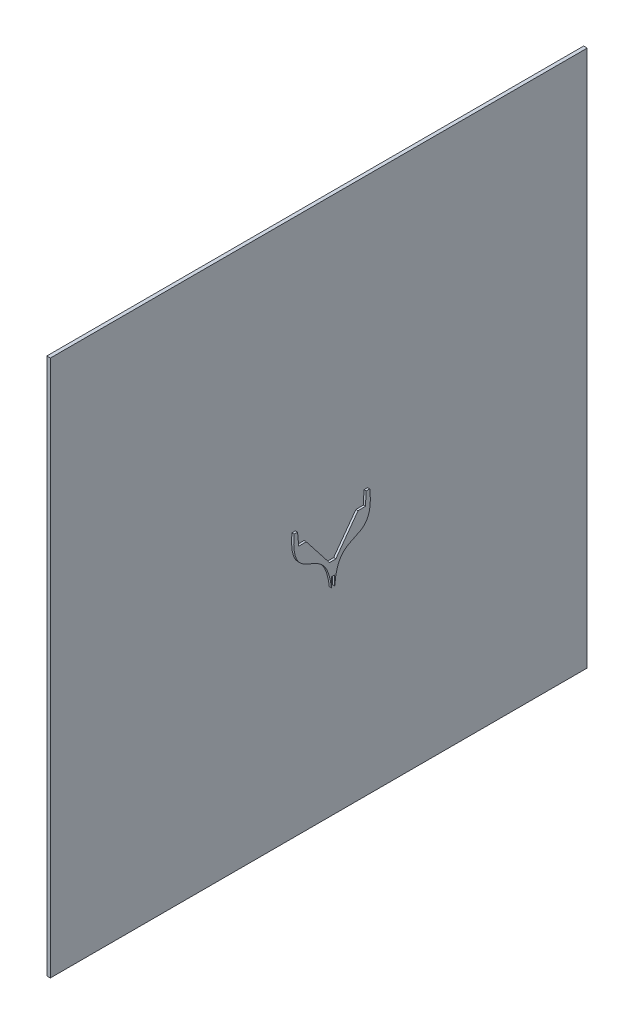
SolidWorks part; units mm, degrees
ref_plane "Plan de face" through (0, 0, 0) normal (0, 0, 1) x (1, 0, 0)
ref_plane "Plan de dessus" through (0, 0, 0) normal (0, 1, 0) x (1, 0, 0)
ref_plane "Plan de droite" through (0, 0, 0) normal (1, 0, 0) x (0, 0, -1)
sketch "Esquisse1" plane through (0, 0, 0) normal (0, 0, 1) x (1, 0, 0)
  point P0 (-20, 0)
  dimension "D1" = 20
sketch3d "Esquisse3D1"
  line L1 (-20, 1121.2893, 777.275) -> (-20, 1121.2893, -722.725)
  line L2 (-20, 1121.2893, 777.275) -> (-20, -378.7107, 777.275)
  line L3 (-20, -378.7107, 777.275) -> (-20, -378.7107, -722.725)
  line L4 (-20, 1121.2893, -722.725) -> (-20, -378.7107, -722.725)
  dimension "D1" = 1500
  dimension "D2" = 1500
extrude "Boss.-Extru.2" add sketch "Esquisse3D1" along direction (1, 0, 0) on the side of the normal blind 10 contours L2 L1 L4 L3
sketch "Esquisse4" plane through (-10, 0, 0) normal (1, 0, 0) x (0, 0, -1)
  line L0 (0, 0) -> (-7.701, 425.1082) construction
  line L1 (169.3944, 339.9131) -> (-188.5193, 333.4294) construction
  line L2 (-187.2006, 249.23) -> (169.0622, 255.6839) construction
  line L3 (-144.268, 175.2448) -> (126.4811, 180.1495) construction
sketch "Esquisse5" plane through (0, 0, 0) normal (1, 0, 0) x (0, 0, -1)
  line L0 (-7.701, 425.1082) -> (0, 0) construction
  line L2 (0, 0) -> (13.2414, 145.149) construction
  line L3 (13.2414, 145.149) -> (-56.4453, 383.7717) construction
  line L4 (-56.4453, 383.7717) -> (120.2156, 187.3517) construction
  line L5 (120.2156, 187.3517) -> (99.0942, 374.657) construction
  line L6 (-8.1043, 252.4744) -> (-1.0453, 252.6023)
  line L8 (99.0942, 374.657) -> (89.0942, 374.4759)
  line L9 (89.0942, 374.4759) -> (87.1184, 338.4227)
  line L10 (169.3944, 339.9131) -> (-188.5193, 333.4294) construction
  line L11 (87.1184, 338.4227) -> (66.3274, 338.046)
  line L12 (66.3274, 338.046) -> (4.2416, 252.6981)
  line L13 (-187.2006, 249.23) -> (169.0622, 255.6839) construction
  line L14 (4.2416, 252.6981) -> (-1.0453, 252.6023)
  line L16 (-144.268, 175.2448) -> (126.4811, 180.1495) construction
  line L18 (0, 0) -> (-18.4898, 144.5742) construction
  line L19 (-18.4898, 144.5742) -> (42.5085, 385.5643) construction
  line L20 (42.5085, 385.5643) -> (-126.9224, 182.8747) construction
  line L21 (-126.9224, 182.8747) -> (-112.5988, 370.8221) construction
  line L23 (-13.3913, 252.3787) -> (-8.1043, 252.4744)
  line L24 (-78.5275, 335.4219) -> (-13.3913, 252.3787)
  line L25 (-99.3186, 335.0453) -> (-78.5275, 335.4219)
  line L26 (-102.5988, 371.0033) -> (-99.3186, 335.0453)
  line L27 (-112.5988, 370.8221) -> (-102.5988, 371.0033)
  spline S0 degree 4 poles (0, 0) (13.2414, 145.149) (-56.4453, 383.7717) (120.2156, 187.3517) (99.0942, 374.657) knots 0 0 0 0 0 1 1 1 1 1
  spline S1 degree 4 poles (0, 0) (-18.4898, 144.5742) (42.5085, 385.5643) (-126.9224, 182.8747) (-112.5988, 370.8221) knots 0 0 0 0 0 1 1 1 1 1
  point P30 (-3.2209, 177.7999)
  dimension "D1" = 10
extrude "Boss.-Extru.3" add sketch "Esquisse5" along normal blind 6 separate body
sketch "Esquisse6" plane through (6, 0, 0) normal (1, 0, 0) x (0, 0, -1)
  line L0 (-7.9142, 188.3867) -> (-8.4033, 215.3867)
  line L1 (-8.4033, 215.3867) -> (0.5967, 215.5497)
  line L2 (0.5967, 215.5497) -> (1.0858, 188.5497)
  line L3 (1.0858, 188.5497) -> (117.0633, -47.527)
  line L4 (117.0633, -47.527) -> (-85.2277, -65.22)
  line L5 (-85.2277, -65.22) -> (-7.9142, 188.3867)
  line L6 (-7.9142, 188.3867) -> (1.0858, 188.5497) construction
  line L7 (-144.268, 175.2448) -> (126.4811, 180.1495) construction
  spline S0 degree 4 poles (-112.5988, 370.8221) (-126.9224, 182.8747) (42.5085, 385.5643) (-18.4898, 144.5742) (0, 0) knots 0 0 0 0 0 1 1 1 1 1 construction
  spline S1 degree 4 poles (0, 0) (13.2414, 145.149) (-56.4453, 383.7717) (120.2156, 187.3517) (99.0942, 374.657) knots 0 0 0 0 0 1 1 1 1 1 construction
  dimension "D1" = 9
  dimension "D2" = 27
extrude "Enlèv. mat.-Extru.1" cut sketch "Esquisse6" against normal blind 6
